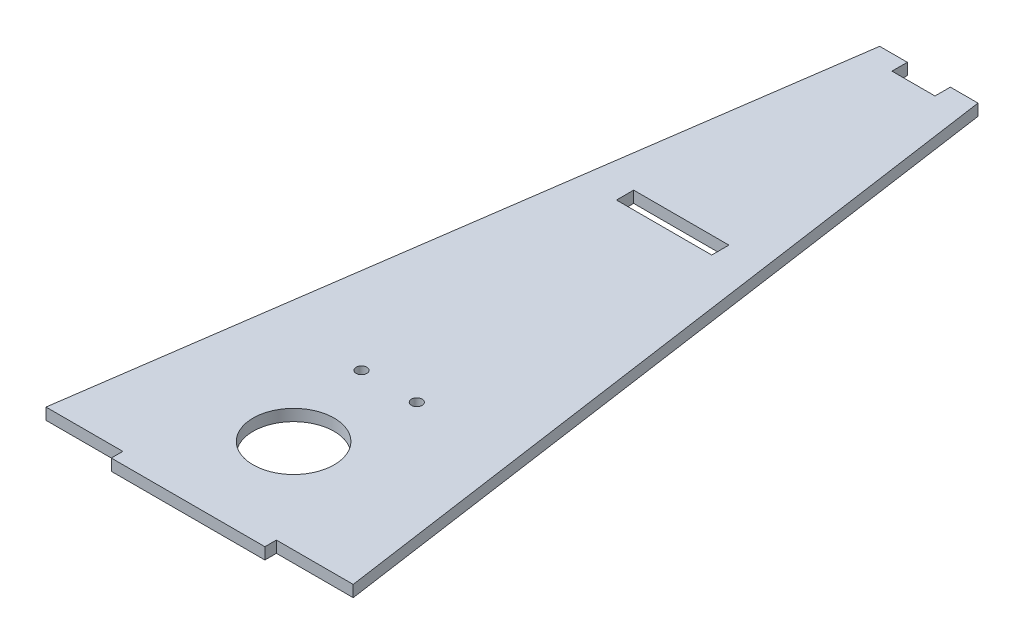
SolidWorks part; units mm, degrees
material "Teak"
ref_plane "Front Plane" through (0, 0, 0) normal (0, 0, 1) x (1, 0, 0)
ref_plane "Top Plane" through (0, 0, 0) normal (0, 1, 0) x (1, 0, 0)
ref_plane "Right Plane" through (0, 0, 0) normal (1, 0, 0) x (0, 0, -1)
sketch "Sketch1" plane through (0, 0, 0) normal (0, 1, 0) x (1, 0, 0)
  line L0 (0, 0) -> (-1.8577, 0) construction
  line L1 (0, 0) -> (0, -2.4685) construction
  line L2 (63.5, 0) -> (-63.5, 0)
  line L3 (-63.5, 0) -> (-20.326, 301.4702)
  line L4 (-20.326, 301.4702) -> (20.326, 301.4702)
  line L5 (63.5, 0) -> (20.326, 301.4702)
  point P12 (0, 0)
  point P13 (0, 301.4702)
  dimension "D1" = 63.5
  dimension "D2" = 81.85
  dimension "D3" = 304.546
extrude "Boss-Extrude1" add sketch "Sketch1" along normal blind 4.7625
sketch "Sketch2" plane through (0, 4.7625, 0) normal (0, 1, 0) x (1, 0, 0)
  line L0 (0, 0) -> (0, 301.4702) construction
  line L1 (-63.5, 0) -> (63.5, 0) construction
  line L2 (20.326, 301.4702) -> (-20.326, 301.4702) construction
  line L3 (52.2781, 78.359) -> (-52.2781, 78.359) construction
  line L4 (-20.326, 301.4702) -> (-63.5, 0) construction
  line L5 (63.5, 0) -> (20.326, 301.4702) construction
  line L6 (8.89, 301.4702) -> (-8.89, 301.4702)
  line L7 (-19.685, 199.136) -> (19.685, 199.136)
  line L8 (-19.685, 199.136) -> (-19.685, 192.024)
  line L9 (-19.685, 192.024) -> (19.685, 192.024)
  line L10 (19.685, 199.136) -> (19.685, 192.024)
  line L11 (-19.685, 199.136) -> (19.685, 192.024) construction
  line L12 (-19.685, 192.024) -> (19.685, 199.136) construction
  line L13 (-8.89, 301.4702) -> (-8.89, 295.1202)
  line L14 (-8.89, 295.1202) -> (8.89, 295.1202)
  line L15 (8.89, 301.4702) -> (8.89, 295.1202)
  circle A0 centre (0, 38.862) radius 16.764
  circle A1 centre (-11.43, 78.359) radius 2.2225
  circle A3 centre (11.43, 78.359) radius 2.2225
  point P18 (0, 195.58)
  point P27 (0, 295.1202)
  dimension "D1" = 38.862
  dimension "D2" = 33.528
  dimension "D4" = 4.445
  dimension "D3" = 78.359
  dimension "D5" = 11.43
  dimension "D6" = 195.58
  dimension "D7" = 7.112
  dimension "D8" = 39.37
  dimension "D9" = 8.89
  dimension "D10" = 6.35
extrude "Cut-Extrude1" cut sketch "Sketch2" against normal through all
sketch "Sketch3" plane through (0, 0, 0) normal (0, 0, 1) x (1, 0, 0)
  line L0 (-63.5, 2.3813) -> (63.5, 2.3813) construction
  line L1 (-63.5, 4.7625) -> (-63.5, 0) construction
  line L2 (63.5, 4.7625) -> (63.5, 0) construction
  line L3 (-63.5, 0) -> (63.5, 0) construction
  line L4 (-31.75, 4.7625) -> (31.75, 4.7625)
  line L5 (-31.75, 4.7625) -> (-31.75, 0)
  line L6 (-31.75, 0) -> (31.75, 0)
  line L7 (31.75, 4.7625) -> (31.75, 0)
  line L8 (-31.75, 4.7625) -> (31.75, 0) construction
  line L9 (-31.75, 0) -> (31.75, 4.7625) construction
  point P6 (0, 2.3813)
  dimension "D1" = 63.5
extrude "Boss-Extrude2" add sketch "Sketch3" along normal blind 4.7625
